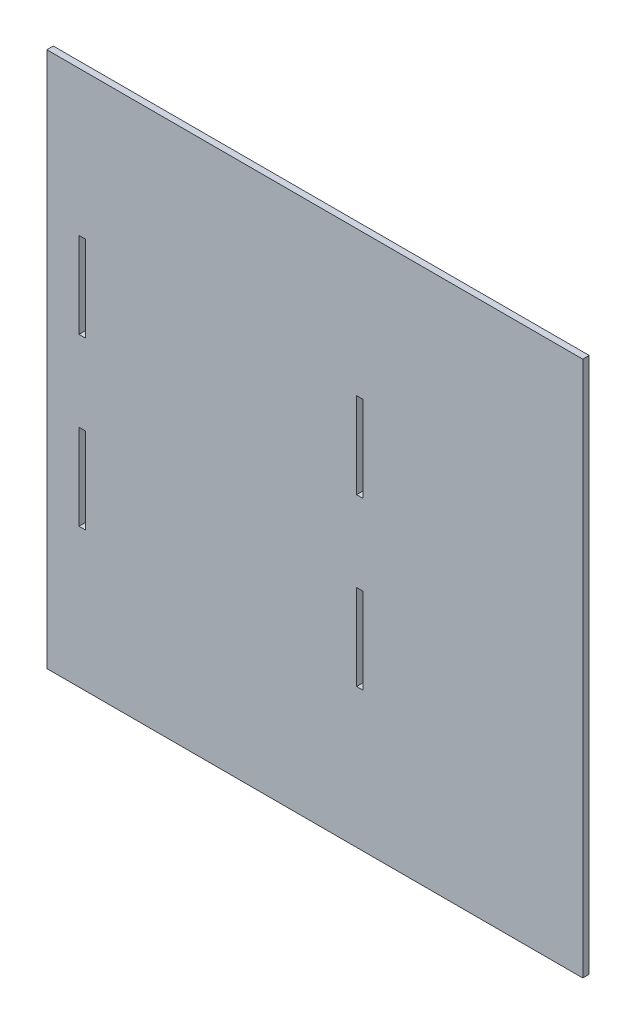
SolidWorks part; units mm, degrees
material "Carvalho"
ref_plane "Plano frontal" through (0, 0, 0) normal (0, 0, 1) x (1, 0, 0)
ref_plane "Plano superior" through (0, 0, 0) normal (0, 1, 0) x (1, 0, 0)
ref_plane "Plano direito" through (0, 0, 0) normal (1, 0, 0) x (0, 0, -1)
sketch "Esboço1" plane through (0, 0, 0) normal (0, 0, 1) x (1, 0, 0)
  line L1 (0, 0) -> (500, 0)
  line L2 (0, 0) -> (0, 500)
  line L3 (0, 500) -> (500, 500)
  line L4 (500, 0) -> (500, 500)
  line L5 (30, 130) -> (36, 130)
  line L6 (30, 130) -> (30, 210)
  line L7 (30, 210) -> (36, 210)
  line L8 (36, 130) -> (36, 210)
  line L9 (30, 285) -> (36, 285)
  line L10 (30, 285) -> (30, 365)
  line L11 (30, 365) -> (36, 365)
  line L12 (36, 285) -> (36, 365)
  line L13 (289, 365) -> (295, 365)
  line L14 (289, 365) -> (289, 285)
  line L15 (289, 285) -> (295, 285)
  line L16 (295, 365) -> (295, 285)
  line L17 (289, 210) -> (295, 210)
  line L18 (289, 210) -> (289, 130)
  line L19 (289, 130) -> (295, 130)
  line L20 (295, 210) -> (295, 130)
  dimension "D1" = 500
  dimension "D2" = 500
  dimension "D3" = 80
  dimension "D4" = 75
  dimension "D5" = 80
  dimension "D6" = 6
  dimension "D7" = 6
  dimension "D8" = 30
  dimension "D9" = 130
  dimension "D10" = 135
  dimension "D11" = 253
  dimension "D12" = 253
  dimension "D13" = 75
  dimension "D14" = 135
extrude "Ressalto-extrusão1" add sketch "Esboço1" along normal blind 6
